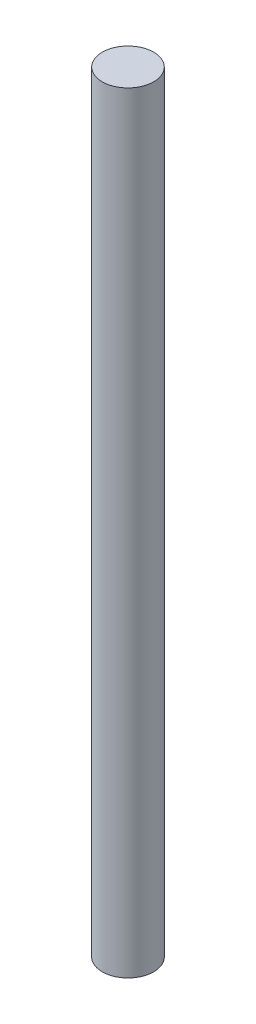
SolidWorks part; units mm, degrees
ref_plane "Front Plane" through (0, 0, 0) normal (0, 0, 1) x (1, 0, 0)
ref_plane "Top Plane" through (0, 0, 0) normal (0, 1, 0) x (1, 0, 0)
ref_plane "Right Plane" through (0, 0, 0) normal (1, 0, 0) x (0, 0, -1)
sketch "Sketch2" plane through (0, 0, 0) normal (0, 1, 0) x (1, 0, 0)
  circle A0 centre (0, 0) radius 5
extrude "Boss-Extrude1" add sketch "Sketch2" along normal blind 150
